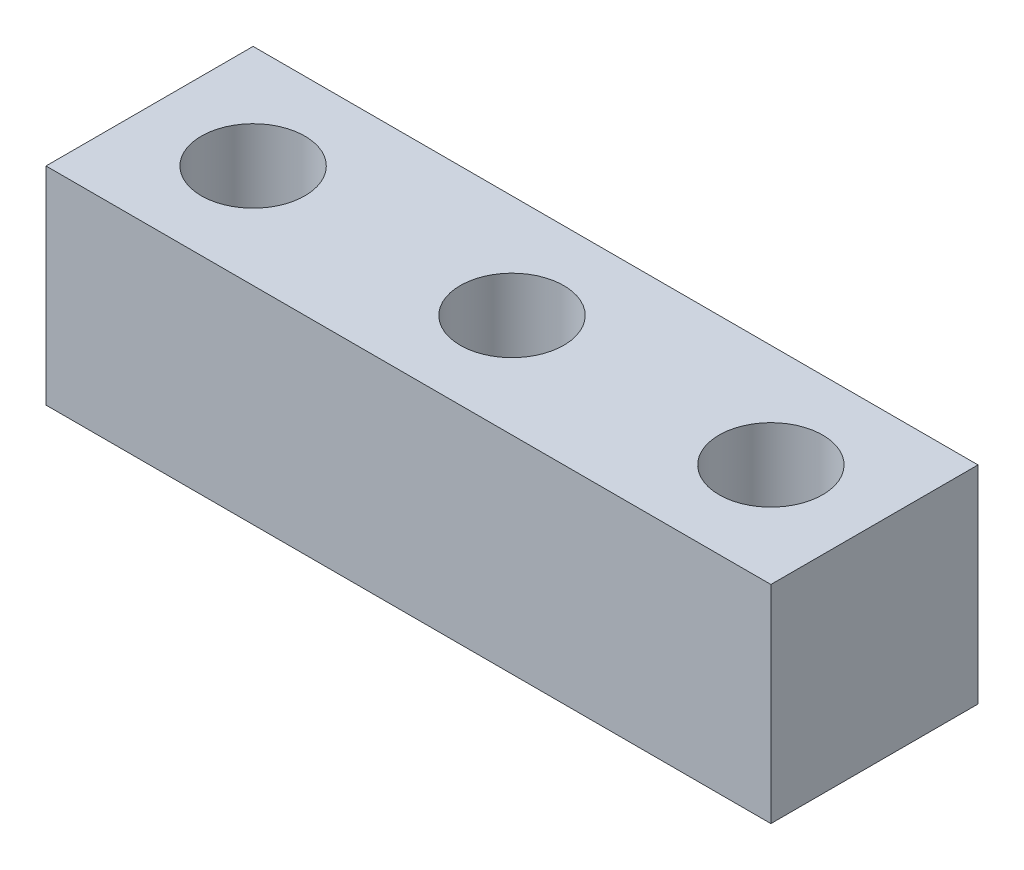
SolidWorks part; units mm, degrees
ref_plane "Front Plane" through (0, 0, 0) normal (0, 0, 1) x (1, 0, 0)
ref_plane "Top Plane" through (0, 0, 0) normal (0, 1, 0) x (1, 0, 0)
ref_plane "Right Plane" through (0, 0, 0) normal (1, 0, 0) x (0, 0, -1)
sketch "Sketch1" plane through (0, 0, 0) normal (0, 1, 0) x (1, 0, 0)
  line L1 (-22.225, -6.35) -> (22.225, -6.35)
  line L2 (-22.225, -6.35) -> (-22.225, 6.35)
  line L3 (-22.225, 6.35) -> (22.225, 6.35)
  line L4 (22.225, -6.35) -> (22.225, 6.35)
  line L5 (-22.225, -6.35) -> (22.225, 6.35) construction
  line L6 (-22.225, 6.35) -> (22.225, -6.35) construction
  point P0 (0, 0)
  dimension "D1" = 44.45
  dimension "D2" = 12.7
extrude "Boss-Extrude1" add sketch "Sketch1" along normal blind 12.7
sketch "Sketch2" plane through (0, 12.7, 0) normal (0, 1, 0) x (1, 0, 0)
  line L2 (-22.225, 6.35) -> (-22.225, -6.35) construction
  circle A0 centre (-15.875, 0) radius 3.175
  circle A1 centre (15.875, 0) radius 3.175
  point P4 (0, 0)
  point P6 (-25.4247, 12.1836)
  dimension "D3" = 6.35
  dimension "D4" = 6.35
  dimension "D1" = 31.75
  dimension "D2" = 6.35
extrude "Cut-Extrude1" cut sketch "Sketch2" against normal blind 12.7
sketch "Sketch3" plane through (0, 12.7, 0) normal (0, 1, 0) x (1, 0, 0)
  circle A0 centre (0, 0) radius 3.175
extrude "Cut-Extrude2" cut sketch "Sketch3" against normal blind 12.7
